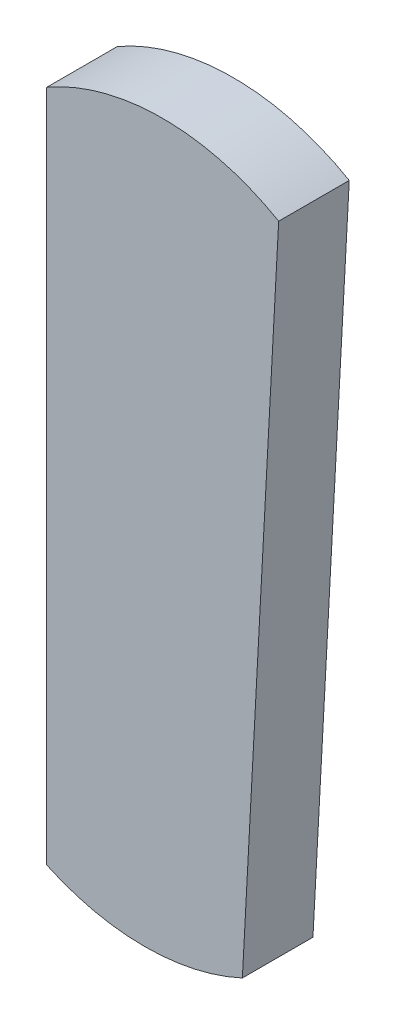
SolidWorks part; units mm, degrees
material "Plain Carbon Steel"
ref_plane "Front Plane" through (0, 0, 0) normal (0, 0, 1) x (1, 0, 0)
ref_plane "Top Plane" through (0, 0, 0) normal (0, 1, 0) x (1, 0, 0)
ref_plane "Right Plane" through (0, 0, 0) normal (1, 0, 0) x (0, 0, -1)
sketch "Sketch1" plane through (0, 0, 0) normal (0, 0, 1) x (1, 0, 0)
  line L0 (0, 54.9) -> (0, -45.9) construction
  line L1 (0, 35.9) -> (0, -30.9)
  line L2 (0, 35.9) -> (23, 35.9)
  line L3 (0, -30.9) -> (19.4, -30.9)
  line L4 (23, 35.9) -> (19.4, -30.9)
  arc A0 (0, 35.9) -> (23, 35.9) centre (11.5, 15.9814) cw
  arc A1 (19.4, -30.9) -> (0, -30.9) centre (9.7, -10.0455) cw
  dimension "D1" = 23
  dimension "D2" = 19.4
extrude "Boss-Extrude1" add sketch "Sketch1" along normal blind 7 contours A0 L2 | L4 L2 L1 L3 | A1 L3
